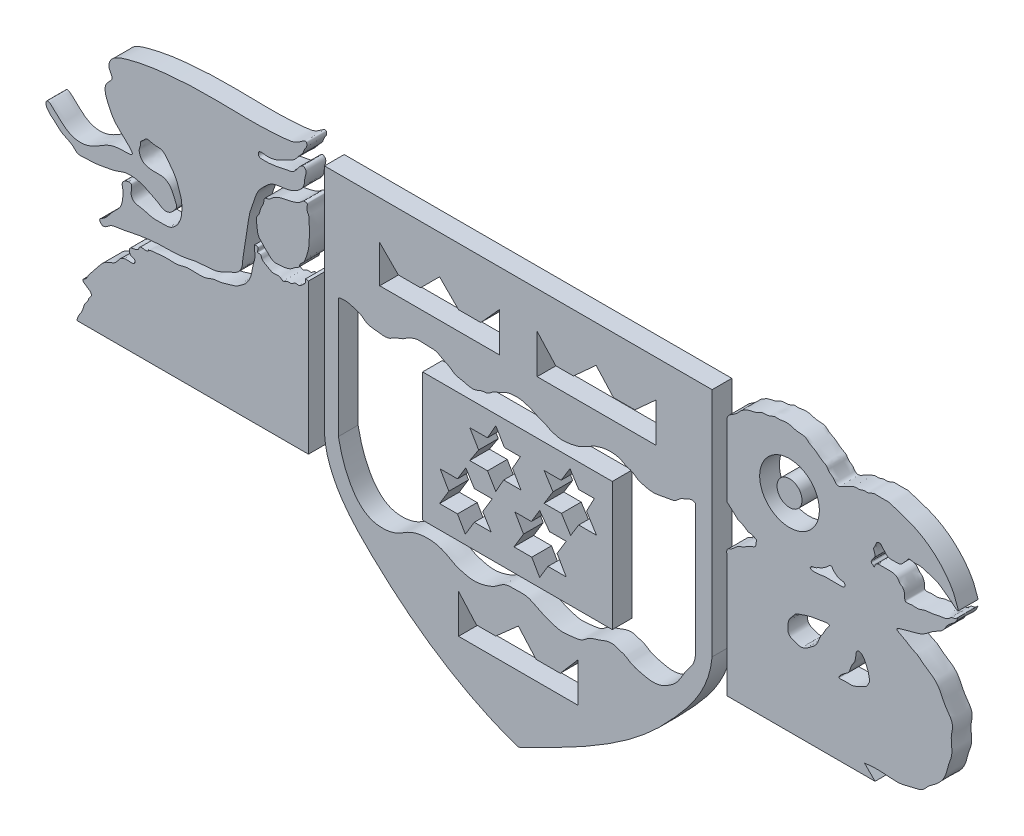
SolidWorks part; units mm, degrees
ref_plane "Front Plane" through (0, 0, 0) normal (0, 0, 1) x (1, 0, 0)
ref_plane "Top Plane" through (0, 0, 0) normal (0, 1, 0) x (1, 0, 0)
ref_plane "Right Plane" through (0, 0, 0) normal (1, 0, 0) x (0, 0, -1)
sketch "Sketch2" plane through (0, 0, 0) normal (0, 0, 1) x (1, 0, 0)
  line L0 (-215.1372, 77.2642) -> (-215.1372, -74.9469)
  line L1 (-215.1372, -74.9469) -> (-450.0201, -74.9469)
  line L2 (-198.8778, -48.2651) -> (-198.8778, 186.6255)
  line L3 (-198.8778, 186.6255) -> (194.5594, 186.6255)
  line L4 (194.5594, 186.6255) -> (194.5594, -48.2651)
  line L5 (93.2386, 55.3239) -> (93.2386, -74.9469)
  line L6 (93.2386, -74.9469) -> (-99.2839, -74.9469)
  line L7 (-99.2839, -74.9469) -> (-99.2839, 55.3239)
  line L8 (-99.2839, 55.3239) -> (93.2386, 55.3239)
  line L9 (-21.3572, 109.2692) -> (-142.8036, 109.2692)
  line L10 (-142.8036, 109.2692) -> (-142.8036, 147.2321)
  line L11 (-142.8036, 147.2321) -> (-123.8222, 128.2507)
  line L12 (-123.8222, 128.2507) -> (-101.35, 128.2507)
  line L13 (-101.35, 128.2507) -> (-82.0804, 147.5203)
  line L14 (-82.0804, 147.5203) -> (-62.8107, 128.2507)
  line L15 (-62.8107, 128.2507) -> (-40.2453, 128.2507)
  line L16 (-40.2453, 128.2507) -> (-21.3572, 149.0856)
  line L17 (-21.3572, 149.0856) -> (-21.3572, 109.2692)
  line L18 (16.9702, 109.2692) -> (137.8333, 109.2692)
  line L19 (137.8333, 109.2692) -> (137.8333, 149.3114)
  line L20 (137.8333, 149.3114) -> (116.1682, 129.6715)
  line L21 (116.1682, 129.6715) -> (94.4529, 129.6715)
  line L22 (94.4529, 129.6715) -> (76.8102, 149.1334)
  line L23 (76.8102, 149.1334) -> (53.8002, 128.2742)
  line L24 (53.8002, 128.2742) -> (35.8796, 128.2742)
  line L25 (35.8796, 128.2742) -> (16.9702, 149.1334)
  line L26 (16.9702, 149.1334) -> (16.9702, 109.2692)
  line L27 (-62.8107, -158.838) -> (58.6041, -158.838)
  line L28 (58.6041, -158.838) -> (58.6041, -118.6788)
  line L29 (58.6041, -118.6788) -> (40.4359, -139.7384)
  line L30 (40.4359, -139.7384) -> (15.8692, -139.7384)
  line L31 (15.8692, -139.7384) -> (-2.1033, -119.4417)
  line L32 (-2.1033, -119.4417) -> (-25.0247, -139.7384)
  line L33 (-25.0247, -139.7384) -> (-44.6466, -139.7384)
  line L34 (-44.6466, -139.7384) -> (-62.8107, -119.2253)
  line L35 (-62.8107, -119.2253) -> (-62.8107, -158.838)
  line L36 (-184.7839, 77.8093) -> (-184.7839, -44.2697)
  line L37 (177.9219, 77.8093) -> (177.9219, -44.2697)
  line L38 (-33.3988, 30.3852) -> (-25.0247, 45.1364)
  line L39 (-25.0247, 45.1364) -> (-16.2196, 30.3852)
  line L40 (-16.2196, 30.3852) -> (0, 30.3852)
  line L41 (0, 30.3852) -> (-8.1098, 16.0997)
  line L42 (-8.1098, 16.0997) -> (0.6485, 1.4268)
  line L43 (0.6485, 1.4268) -> (-17.0156, 1.4268)
  line L44 (-17.0156, 1.4268) -> (-25.0247, -12.6811)
  line L45 (-25.0247, -12.6811) -> (-33.3988, 1.3482)
  line L46 (-33.3988, 1.3482) -> (-51.4405, 1.3482)
  line L47 (-51.4405, 1.3482) -> (-42.4197, 15.1441)
  line L48 (-42.4197, 15.1441) -> (-51.4405, 30.2567)
  line L49 (-51.4405, 30.2567) -> (-33.3988, 30.3852)
  line L50 (24.0411, 1.4268) -> (33.0689, 16.0997)
  line L51 (33.0689, 16.0997) -> (24.0411, 30.3852)
  line L52 (24.0411, 30.3852) -> (41.2768, 30.3852)
  line L53 (41.2768, 30.3852) -> (50.3528, 45.1364)
  line L54 (50.3528, 45.1364) -> (59.1724, 31.1803)
  line L55 (59.1724, 31.1803) -> (75.0124, 31.1803)
  line L56 (75.0124, 31.1803) -> (67.0924, 16.0997)
  line L57 (67.0924, 16.0997) -> (77.2667, 0)
  line L58 (77.2667, 0) -> (59.1724, 0)
  line L59 (59.1724, 0) -> (50.9753, -13.3227)
  line L60 (50.9753, -13.3227) -> (41.6543, 1.4268)
  line L61 (41.6543, 1.4268) -> (24.0411, 1.4268)
  line L62 (19.5246, -7.0232) -> (11.078, -20.9755)
  line L63 (11.078, -20.9755) -> (-5.5411, -20.9755)
  line L64 (-5.5411, -20.9755) -> (3.137, -36.0467)
  line L65 (3.137, -36.0467) -> (-6.5848, -52.1054)
  line L66 (-6.5848, -52.1054) -> (11.5392, -52.1054)
  line L67 (11.5392, -52.1054) -> (19.5246, -65.9733)
  line L68 (19.5246, -65.9733) -> (27.9801, -52.0062)
  line L69 (27.9801, -52.0062) -> (46.4812, -52.0062)
  line L70 (46.4812, -52.0062) -> (37.2306, -35.9411)
  line L71 (37.2306, -35.9411) -> (46.4812, -20.6609)
  line L72 (46.4812, -20.6609) -> (29.6207, -20.6609)
  line L73 (29.6207, -20.6609) -> (19.5246, -7.0232)
  line L74 (-63.8781, -20.9755) -> (-81.4508, -20.9755)
  line L75 (-81.4508, -20.9755) -> (-72.6644, -36.2345)
  line L76 (-72.6644, -36.2345) -> (-82.0804, -51.7881)
  line L77 (-82.0804, -51.7881) -> (-63.8781, -51.7881)
  line L78 (-63.8781, -51.7881) -> (-55.8947, -65.6526)
  line L79 (-55.8947, -65.6526) -> (-46.7831, -50.6019)
  line L80 (-46.7831, -50.6019) -> (-29.7564, -50.6019)
  line L81 (-29.7564, -50.6019) -> (-38.2698, -36.8433)
  line L82 (-38.2698, -36.8433) -> (-28.6635, -20.9755)
  line L83 (-28.6635, -20.9755) -> (-46.7831, -20.9755)
  line L84 (-46.7831, -20.9755) -> (-55.4163, -7.0232)
  line L85 (-55.4163, -7.0232) -> (-63.8781, -20.9755)
  line L86 (209.5236, 168.4535) -> (209.5236, 95.674)
  line L87 (209.5236, 50.21) -> (209.5236, -74.9469)
  line L88 (209.5236, -74.9469) -> (359.9567, -74.9469)
  line L89 (359.9567, -74.9469) -> (349.2206, -64.2108)
  circle A0 centre (273.1415, 134.9863) radius 12.6897
  circle A1 centre (273.1415, 134.9863) radius 30.288
  spline S0 degree 3 poles (-481.6838, 97.9855) (-481.1686, 109.2139) (-458.8842, 78.7668) (-432.2978, 84.6758) (-415.3851, 99.4801) (-383.802, 96.0538) (-410.3287, 114.896) (-417.7314, 129.6658) (-425.6181, 146.3468) (-411.7703, 155.3903) (-419.1213, 163.1906) (-415.6968, 174.0032) (-403.8671, 179.0192) (-389.0534, 182.7717) (-370.9088, 186.1491) (-350.3654, 188.189) (-325.9159, 189.5848) (-301.2341, 189.3671) (-275.3819, 188.7985) (-254.4865, 189.082) (-236.5609, 190.5012) (-226.4732, 192.4326) (-216.8608, 201.2071) (-216.4924, 194.1933) (-219.5765, 191.3548) (-220.2906, 186.6771) (-224.8567, 182.8078) (-228.5214, 176.666) (-236.7832, 172.7326) (-246.5316, 167.4529) (-255.5129, 165.0371) (-265.9387, 167.4603) (-266.2495, 160.8937) (-257.8218, 160.4797) (-248.9482, 161.2808) (-238.5704, 163.896) (-227.5443, 165.279) (-222.5828, 178.6879) (-216.5087, 172.3772) (-219.372, 166.5665) (-218.7208, 158.9455) (-225.3493, 150.9425) (-237.4815, 145.7841) (-251.4122, 146.2964) (-259.735, 138.0605) (-267.4674, 130.6535) (-270.4753, 119.4147) (-275.204, 107.5973) (-276.1987, 98.2613) (-278.3282, 87.6303) (-279.1008, 77.052) (-282.077, 65.5098) (-281.8236, 56.1921) (-286.4704, 48.3421) (-296.362, 45.288) (-308.6114, 37.5073) (-325.5855, 39.0464) (-343.4863, 33.7176) (-359.9554, 34.1106) (-374.5377, 33.2942) (-389.8947, 31.2009) (-403.6843, 27.6252) (-416.7161, 26.6361) (-423.1305, 18.7346) (-428.6374, 25.9698) (-420.5118, 29.2) (-417.0141, 35.5428) (-410.6912, 41.7177) (-404.8713, 47.3766) (-403.5679, 55.8541) (-402.9873, 63.0347) (-405.7642, 71.3845) (-392.65, 75.5095) (-395.3366, 66.5932) (-395.1173, 61.449) (-391.128, 57.0647) (-382.9451, 56.92) (-374.2352, 52.9811) (-364.4716, 53.929) (-356.4468, 53.3119) (-350.2782, 57.3274) (-346.1057, 62.856) (-343.7117, 70.0952) (-343.6262, 77.5663) (-343.792, 84.2958) (-346.3296, 91.1063) (-348.3693, 98.1121) (-352.3991, 105.3601) (-356.8118, 110.4816) (-359.969, 115.0122) (-364.6707, 119.2408) (-371.8169, 117.6815) (-379.4146, 121.5116) (-382.546, 116.828) (-386.3377, 115.1333) (-385.4465, 110.669) (-387.0035, 107.9161) (-386.9218, 104.4107) (-385.7325, 101.4074) (-383.3289, 97.6107) (-377.084, 95.1772) (-369.5759, 95.1569) (-362.0201, 95.431) (-356.9546, 92.1652) (-353.9578, 88.4603) (-352.21, 83.928) (-350.3508, 80.3302) (-348.8858, 76.9159) (-349.2581, 73.625) (-351.6307, 71.1467) (-354.3781, 67.6488) (-359.5109, 65.5933) (-364.4815, 67.4179) (-368.7298, 70.8444) (-374.0969, 72.8061) (-379.1033, 75.9451) (-384.0337, 77.7485) (-389.15, 79.5561) (-395.2265, 80.0253) (-401.4198, 79.7997) (-407.1079, 77.4707) (-413.0764, 75.5422) (-418.8819, 74.4965) (-425.2832, 73.1779) (-433.5228, 72.1892) (-441.7338, 72.2123) (-449.4245, 71.3966) (-452.4807, 74.8747) (-457.2826, 79.0979) (-465.7959, 81.4949) (-471.3355, 87.9923) (-476.2555, 91.4497) (-479.0958, 94.8706) (-481.6838, 97.9855) (-481.1686, 109.2139) (-458.8842, 78.7668) knots -0.009663 -0.0058 -0.002444 0 0.017705 0.043382 0.063353 0.07559 0.09589 0.105371 0.122865 0.129645 0.136402 0.142815 0.154225 0.16544 0.180768 0.198972 0.215876 0.24048 0.259274 0.278734 0.292309 0.301056 0.30813 0.310916 0.313832 0.318232 0.32156 0.328065 0.335249 0.343314 0.354742 0.360031 0.362485 0.366861 0.376163 0.386746 0.392023 0.403564 0.405219 0.41082 0.416796 0.423753 0.434079 0.448614 0.45498 0.461869 0.474526 0.482328 0.493002 0.497202 0.508807 0.518781 0.526208 0.531078 0.539795 0.550325 0.565936 0.579331 0.595672 0.60575 0.614994 0.633506 0.640077 0.647401 0.65101 0.65491 0.663775 0.669553 0.676301 0.682985 0.689559 0.694461 0.701722 0.707403 0.710306 0.714724 0.720005 0.729592 0.737422 0.743696 0.748614 0.754589 0.760379 0.766858 0.772776 0.776613 0.784493 0.790565 0.796683 0.800889 0.80421 0.811211 0.818164 0.819669 0.82442 0.826202 0.829882 0.831776 0.834556 0.837703 0.84244 0.849959 0.856253 0.86021 0.864171 0.867706 0.871987 0.874098 0.876683 0.87948 0.882251 0.887599 0.891481 0.894602 0.900885 0.905226 0.908976 0.91367 0.918397 0.923777 0.928593 0.93327 0.939087 0.942952 0.949254 0.959103 0.963941 0.966225 0.969932 0.979611 0.986702 0.990337 0.9942 0.997556 1 1.017705 1.043382 1.063353 only from (-481.3655, 101.5851) to (-481.3655, 101.5851)
  spline S1 degree 3 poles (-218.4258, 145.0577) (-215.1861, 145.6277) (-217.9586, 139.0421) (-214.4707, 135.5343) (-214.6548, 130.8669) (-214.5201, 126.6626) (-214.0037, 122.5879) (-214.2063, 118.5026) (-214.3431, 114.1944) (-214.3829, 109.6121) (-215.2054, 104.3092) (-216.5316, 99.7852) (-218.0977, 95.4284) (-219.456, 91.0718) (-223.7827, 88.9185) (-224.4921, 83.9458) (-229.0184, 82.6197) (-232.1124, 79.2985) (-238.1302, 76.8659) (-243.8862, 76.6709) (-249.9738, 76.1958) (-253.6384, 78.4092) (-256.4027, 81.7487) (-259.8725, 84.2045) (-262.0072, 87.2883) (-265.0369, 89.7982) (-266.9385, 93.712) (-267.0928, 98.4317) (-268.0942, 103.0975) (-268.1434, 107.8479) (-264.3719, 111.5098) (-264.2405, 117.6013) (-259.9737, 121.9169) (-260.6973, 128.5175) (-255.0684, 128.5805) (-251.9602, 132.2562) (-247.5952, 134.8321) (-243.1532, 136.4237) (-237.5518, 137.4189) (-232.0862, 138.6965) (-226.3652, 140.4649) (-222.7816, 142.6752) (-220.4225, 145.2934) (-218.4258, 145.0577) (-215.1861, 145.6277) (-217.9586, 139.0421) knots -0.030519 -0.013616 -0.008398 0 0.028025 0.053073 0.072938 0.095208 0.117974 0.134884 0.157284 0.183516 0.204379 0.238643 0.254742 0.275232 0.305719 0.319238 0.345145 0.36747 0.388393 0.441113 0.45498 0.479822 0.501596 0.521231 0.543541 0.557889 0.580573 0.606863 0.628752 0.654184 0.67366 0.704075 0.739613 0.763031 0.782855 0.808328 0.834514 0.858982 0.87968 0.920777 0.944636 0.969481 0.986384 0.991602 1 1.028025 1.053073 1.072938 only from (-216.9511, 145.125) to (-216.9511, 145.125)
  spline S2 degree 3 poles (-450.0201, -74.9469) (-449.7833, -69.8714) (-444.0549, -65.3486) (-443.0964, -56.8405) (-438.9983, -53.1908) (-438.2034, -48.7323) (-435.3945, -46.551) (-435.3783, -43.6446) (-437.4013, -41.8397) (-439.7511, -40.624) (-441.572, -38.7287) (-444.1546, -37.8382) (-444.1742, -35.157) (-440.8316, -34.101) (-439.2185, -30.4044) (-436.6135, -26.7596) (-433.6656, -22.9691) (-430.0858, -19.2329) (-427.1125, -14.7509) (-423.7177, -10.9688) (-418.3093, -7.3212) (-410.4912, -5.8224) (-406.2942, 3.1611) (-398.6163, 4.2476) (-392.5475, 3.0003) (-391.0583, 5.6099) (-390.8909, 8.4538) (-395.768, 8.4722) (-397.0769, 12.3869) (-396.3342, 17.8503) (-388.1088, 15.658) (-386.3663, 23.816) (-379.9418, 20.179) (-376.3146, 24.0607) (-369.837, 24.5051) (-363.1973, 25.4309) (-354.9583, 25.4189) (-347.3281, 24.604) (-339.6444, 27.9365) (-331.6742, 27.2721) (-324.6166, 27.2279) (-317.8686, 27.9201) (-311.8804, 31.1511) (-303.0969, 31.1188) (-295.3957, 34.5468) (-288.1706, 35.7986) (-284.5767, 38.9828) (-278.8788, 42.3151) (-274.7337, 48.4085) (-272.4926, 56.1242) (-271.7178, 62.4445) (-269.8153, 68.2732) (-269.0437, 72.8088) (-269.8853, 76.2187) (-269.9418, 78.6954) (-269.6012, 81.0098) (-270.0389, 81.5672) knots 0 0 0 0 0.047872 0.066459 0.082725 0.1008 0.10993 0.116246 0.127541 0.135109 0.143157 0.154807 0.157507 0.168138 0.183324 0.197615 0.213721 0.232111 0.250063 0.268335 0.283322 0.316033 0.343418 0.373101 0.390343 0.396144 0.401833 0.415503 0.431642 0.437475 0.467947 0.480849 0.503639 0.515548 0.530332 0.567146 0.584761 0.613988 0.643782 0.666902 0.694106 0.716003 0.734802 0.761919 0.802723 0.820049 0.83461 0.850441 0.887131 0.905259 0.932159 0.951457 0.967645 0.978258 0.985865 0.995157 0.995157 0.995157 0.995157
  spline S3 degree 3 poles (-270.0389, 81.5672) (-269.813, 81.6505) (-265.2301, 82.3962) (-266.4571, 79.5425) (-267.1731, 75.8277) (-263.4193, 77.2055) (-262.7532, 71.9495) (-256.9908, 69.7885) (-251.393, 64.9997) (-244.7076, 67.7451) (-240.6131, 62.8323) (-236.7416, 67.34) (-232.0008, 65.3627) (-229.1792, 69.6888) (-224.3129, 67.7217) (-220.6226, 71.6415) (-217.338, 74.3201) (-218.3249, 78.039) (-216.9946, 77.8847) (-215.7405, 77.4198) (-215.1372, 77.2642) knots -0.003182 -0.003182 -0.003182 -0.003182 0 0.058316 0.090029 0.118904 0.171051 0.251574 0.371644 0.456215 0.511489 0.583929 0.637245 0.696303 0.756006 0.818658 0.905355 0.924418 0.939066 0.955633 0.955633 0.955633 0.955633
  spline S4 degree 3 poles (-198.8778, -48.2651) (-197.8829, -70.5276) (-183.2427, -98.6357) (-119.714, -164.8031) (-60.9294, -205.761) (-2.1033, -226.0092) knots 0 0 0 0 0.239264 0.32803 1 1 1 1
  spline S5 degree 3 poles (194.5594, -48.2651) (191.8103, -80.0075) (168.9238, -107.5676) (106.1674, -173.9926) (47.7428, -201.4292) (-2.1033, -226.0092) knots 0 0 0 0 0.32923 0.37905 1 1 1 1
  spline S6 degree 3 poles (-184.7839, 77.8093) (-178.2736, 79.9035) (-170.2532, 77.3879) (-161.0664, 74.1337) (-157.1169, 70.1386) (-151.7955, 68.4188) (-146.2153, 68.1313) (-139.9566, 67.1013) (-133.1286, 67.0141) (-127.7425, 71.6291) (-122.3777, 72.8669) (-117.3548, 75.3022) (-113.5226, 78.6078) (-109.328, 79.7167) (-104.4843, 81.7244) (-97.7491, 80.4562) (-90.6622, 80.9818) (-84.9655, 80.3703) (-81, 78.0091) (-77.1355, 75.8296) (-72.9226, 74.2394) (-69.7028, 71.9017) (-65.386, 68.5281) (-58.9667, 68.3927) (-52.229, 65.9003) (-45.4336, 65.6098) (-39.4709, 69.2945) (-32.5296, 68.8249) (-28.1077, 74.0789) (-22.1539, 75.529) (-16.9813, 78.3978) (-11.8655, 80.7476) (-6.3963, 80.9548) (-1.4348, 81.2934) (2.665, 80.4476) (6.4758, 79.3278) (10.1203, 78.2732) (14.1707, 76.2635) (18.2619, 74.2933) (22.6036, 72.719) (26.7415, 71.2081) (30.732, 68.5976) (35.546, 67.3716) (40.4297, 66.1054) (45.7199, 66.279) (51.5592, 67.087) (57.4292, 68.2664) (62.0539, 70.1603) (65.5486, 72.4365) (69.5242, 73.729) (73.3108, 76.8372) (77.2695, 78.1243) (85.3846, 80.7019) (94.0154, 81.3495) (103.0334, 78.6078) (106.8349, 75.7498) (111.5711, 74.9361) (115.5466, 72.6964) (119.3721, 69.501) (126.3056, 67.7099) (133.2599, 65.8056) (141.6392, 67.0709) (148.8073, 68.8849) (157.1521, 69.2356) (161.8434, 75.1226) (169.2964, 77.2582) (174.6275, 81.1652) (177.9219, 77.8093) knots 0 0 0 0 0.049408 0.065122 0.074372 0.092394 0.106765 0.117844 0.14218 0.155822 0.171146 0.184312 0.199027 0.209637 0.217701 0.23937 0.260408 0.273654 0.282771 0.295927 0.30826 0.317462 0.326842 0.350181 0.364489 0.383112 0.400305 0.417495 0.43281 0.449694 0.46396 0.478948 0.492747 0.506085 0.517509 0.525005 0.53703 0.546899 0.560103 0.572321 0.582811 0.594264 0.609033 0.621099 0.633346 0.6498 0.667026 0.679735 0.688384 0.699341 0.711839 0.725848 0.731279 0.77823 0.789511 0.804052 0.814255 0.826241 0.839144 0.852468 0.881209 0.894273 0.917552 0.939885 0.954673 0.972449 1 1 1 1
  spline S7 degree 3 poles (209.5236, 95.674) (212.5405, 93.3286) (216.2863, 89.7451) (221.5347, 84.4717) (227.1006, 83.5216) (230.6308, 79.3938) (235.3227, 79.946) (237.3678, 78.0388) (240.263, 77.1889) (238.5806, 74.0913) (239.2501, 71.402) (236.8882, 69.3307) (233.1389, 68.6546) (229.4752, 65.9879) (225.2648, 63.5187) (221.4707, 62.8181) (218.7229, 60.2311) (216.1788, 57.9819) (213.7106, 56.0047) (210.0409, 55.016) (208.8972, 51.998) (209.5236, 50.21) knots 0 0 0 0 0.140698 0.20272 0.27294 0.34541 0.38802 0.434701 0.45017 0.487486 0.528266 0.550953 0.595482 0.670909 0.718195 0.780085 0.810483 0.858459 0.909934 0.926876 1 1 1 1
  spline S8 degree 3 poles (-184.7839, -44.2697) (-181.7088, -61.1886) (-169.8303, -100.1744) (-136.5071, -103.015) (-124.0018, -99.6314) (-111.7128, -90.5566) (-97.7814, -87.5618) (-84.5209, -89.0586) (-75.9028, -92.1475) (-67.7849, -97.4351) (-58.0622, -100.6848) (-46.9542, -103.0273) (-35.54, -100.778) (-24.7117, -96.5867) (-16.4137, -88.639) (-4.6554, -89.1582) (6.7166, -87.9784) (17.8071, -94.4216) (28.9505, -99.0034) (41.4, -103.2427) (52.4745, -101.3014) (63.0582, -100.4236) (69.7589, -93.0963) (78.5763, -91.56) (85.8589, -88.237) (93.4564, -86.5255) (100.2928, -89.1975) (106.7757, -91.1425) (113.3796, -96.4378) (122.1179, -98.2392) (132.394, -100.8605) (142.436, -100.1127) (151.2298, -94.9571) (158.6125, -89.3821) (163.7989, -81.0288) (168.8305, -72.345) (178.3532, -61.9741) (177.9347, -50.8033) (177.9219, -44.2697) knots 0 0 0 0 0.151714 0.184463 0.215868 0.236778 0.286538 0.30644 0.326271 0.347459 0.37124 0.394882 0.422889 0.447853 0.472851 0.495567 0.523749 0.548118 0.578983 0.60602 0.634174 0.654028 0.674894 0.696728 0.712285 0.72918 0.747028 0.760411 0.774532 0.802842 0.818868 0.846204 0.867455 0.886772 0.907773 0.932716 0.954701 1 1 1 1
  spline S9 degree 3 poles (309.8333, 34.1404) (316.6146, 41.2133) (303.7301, 38.812) (297.5827, 37.9698) (290.7838, 36.2283) (284.7446, 34.028) (278.8715, 32.1557) (276.4822, 28.1432) (273.6412, 25.4911) (271.8583, 21.9888) (271.5257, 17.4086) (270.9, 12.7769) (274.0457, 8.4589) (278.4602, 7.6459) (282.0627, 5.453) (286.3477, 5.5808) (290.389, 7.1494) (294.0315, 10.0777) (298.1916, 12.8743) (302.0858, 17.6088) (303.6178, 24.005) (308.1075, 29.2976) (309.8333, 34.1404) (316.6146, 41.2133) (303.7301, 38.812) knots -0.144306 -0.096104 -0.040352 0 0.085362 0.137297 0.189091 0.255237 0.30617 0.336249 0.370221 0.40499 0.432327 0.487231 0.517287 0.557452 0.596745 0.621659 0.663201 0.704644 0.739875 0.790531 0.855694 0.903896 0.959648 1 1.085362 1.137297 1.189091 only from (313.5092, 38.779) to (313.5092, 38.779)
  spline S10 degree 3 poles (327.1954, -2.1998) (320.4529, -3.3926) (328.3798, 4.5178) (333.6973, 6.801) (334.9591, 12.1651) (336.7735, 16.4227) (339.4403, 19.546) (340.0131, 22.952) (340.6717, 26.3499) (340.3976, 30.0629) (343.7779, 31.5214) (346.957, 30.2022) (349.3102, 26.758) (351.0622, 22.5456) (353.0966, 18.2625) (353.6496, 14.1079) (354.9822, 10.1264) (352.7781, 7.3256) (351.9419, 4.1499) (348.8486, 2.9463) (346.2825, 1.3535) (343.4885, 0.1584) (340.5104, -1.1685) (337.0704, -2.6599) (333.0722, -2.1703) (330.0308, -2.2837) (327.1954, -2.1998) (320.4529, -3.3926) (328.3798, 4.5178) knots -0.088046 -0.056647 -0.043591 0 0.081736 0.133987 0.190844 0.228094 0.273758 0.308804 0.327816 0.379241 0.399302 0.425337 0.474278 0.518835 0.562011 0.613036 0.645893 0.676772 0.712537 0.736357 0.769865 0.80361 0.825904 0.867284 0.911954 0.943353 0.956409 1 1.081736 1.133987 1.190844 only from (323.727, -2.2577) to (323.727, -2.2577)
  spline S11 degree 3 poles (316.1314, 92.1618) (313.5969, 91.9591) (312.1142, 89.8009) (309.7031, 88.0861) (307.4849, 86.6279) (305.2156, 84.8586) (302.3665, 84.5308) (299.5874, 81.9083) (295.8269, 82.5552) (292.5785, 78.0037) (303.5528, 78.2401) (308.2952, 79.6506) (313.9146, 79.4569) (318.5657, 79.4715) (323.1132, 79.6003) (326.5095, 79.2857) (329.6202, 80.081) (329.472, 84.5246) (325.4535, 84.5556) (322.1751, 85.2977) (320.2667, 87.1881) (318.0856, 88.4831) (317.0279, 90.0964) (316.1314, 92.1618) (313.5969, 91.9591) (312.1142, 89.8009) knots -0.073572 -0.035714 -0.013755 0 0.049661 0.077696 0.112101 0.150352 0.184064 0.215872 0.288688 0.300787 0.407002 0.496219 0.54632 0.609677 0.675012 0.71584 0.741618 0.783753 0.828468 0.86941 0.912101 0.926428 0.964286 0.986245 1 1.049661 1.077696 1.112101 only from (314.703, 91.9811) to (314.703, 91.9811)
  spline S12 degree 3 poles (349.2206, -64.2108) (357.6678, -62.7692) (369.1852, -63.3622) (385.8839, -64.9292) (396.7166, -61.0256) (408.3955, -59.459) (413.9001, -51.6344) (420.9272, -47.3399) (427.3148, -41.4228) (432.4217, -33.2786) (433.9871, -23.0511) (438.045, -14.771) (437.9186, -5.339) (436.4597, 3.5502) (439.67, 12.7728) (436.0968, 20.5289) (430.9435, 26.7364) (427.5117, 34.3397) (423.5745, 42.2834) (416.8083, 47.974) (408.9967, 52.3363) (403.4077, 58.1019) (396.7612, 60.284) (391.6128, 64.2264) (387.0376, 66.359) (379.1841, 70.4715) (388.9484, 72.7951) (394.0051, 74.1679) (400.8106, 76.2129) (410.0698, 78.443) (418.1157, 87.0112) (429.1668, 90.9189) (432.7149, 98.8096) (438.2113, 103.1128) (441.8984, 105.4571) (445.2039, 112.8661) (441.6058, 108.049) (437.5439, 108.7537) (434.426, 104.6425) (429.7226, 103.575) (424.3094, 102.9872) (417.9422, 101.179) (410.7436, 101.2765) (403.7022, 97.7816) (397.6085, 99.41) (388.9998, 96.9927) (390.5204, 104.2817) (389.0097, 107.9164) (387.6481, 110.1566) (384.9289, 111.4047) (383.5985, 114.6865) (379.86, 117.4587) (374.6757, 117.751) (369.5742, 117.6022) (364.4899, 117.8077) (359.9251, 117.1388) (359.1975, 111.7612) (357.7519, 114.5284) (355.2895, 115.38) (357.2693, 118.931) (358.5669, 120.8593) (360.2939, 122.2591) (359.83, 125.4921) (357.5976, 128.8901) (360.63, 132.5619) (361.193, 136.8805) (366.4448, 136.9643) (367.532, 133.5834) (370.2039, 132.0081) (371.9669, 128.8722) (376.22, 128.1182) (379.8101, 128.3306) (383.353, 128.1509) (386.9877, 129.0128) (389.1993, 132.4753) (392.0009, 134.3059) (393.7186, 138.6607) (399.2047, 136.7104) (405.8663, 137.7322) (413.8728, 135.0197) (421.5025, 132.9563) (427.4957, 129.1889) (431.5249, 125.993) (436.6567, 122.6414) (439.264, 119.7973) (445.959, 115.1425) (441.9921, 123.3185) (440.8134, 128.4315) (428.894, 150.3064) (408.7676, 166.5233) (386.7343, 173.1956) (381.5526, 175.3786) (377.2807, 175.9296) (373.6089, 177.8271) (369.5811, 177.3352) (365.9159, 177.5156) (362.3611, 177.4022) (358.9441, 177.7555) (355.8292, 176.2924) (352.6226, 174.7635) (348.378, 175.6809) (344.5263, 173.242) (339.0954, 174.1103) (335.0448, 171.5105) (329.9293, 169.5169) (326.5201, 167.0923) (322.2711, 165.5237) (319.0523, 167.9157) (317.2942, 171.4903) (312.9285, 173.3241) (311.4376, 177.7123) (307.1668, 179.6382) (303.1905, 182.2204) (299.7781, 185.5729) (295.7991, 187.3464) (292.6916, 189.1298) (289.709, 192.6889) (284.5537, 192.9309) (279.5994, 193.224) (274.784, 195.0184) (268.7906, 196.0643) (263.0022, 194.1847) (257.5457, 195.1895) (252.391, 191.5014) (245.6596, 192.9019) (240.4389, 189.1604) (235.5233, 187.9758) (230.726, 187.0965) (227.3483, 184.94) (223.7799, 183.1541) (221.1868, 179.6089) (215.583, 174.9775) (210.2448, 172.9302) (209.5236, 168.4535) knots 0 0 0 0 0.031361 0.043465 0.061521 0.074158 0.084973 0.095187 0.10474 0.117217 0.130046 0.142913 0.150736 0.164686 0.176248 0.184988 0.19487 0.206408 0.215856 0.227585 0.238505 0.249278 0.256639 0.264308 0.272368 0.278549 0.286957 0.295021 0.302068 0.312509 0.330138 0.344439 0.353291 0.36127 0.368641 0.374074 0.377474 0.38305 0.388661 0.394518 0.400489 0.409061 0.418936 0.427069 0.436548 0.443557 0.451728 0.455346 0.458867 0.460991 0.466115 0.471206 0.477466 0.484934 0.490191 0.496906 0.500021 0.502694 0.504368 0.509063 0.512754 0.51437 0.516689 0.523824 0.527197 0.533341 0.537535 0.542148 0.54487 0.548855 0.554801 0.559382 0.56247 0.568088 0.572092 0.577186 0.580516 0.587439 0.593758 0.60661 0.617529 0.623293 0.632704 0.636963 0.645412 0.650355 0.657189 0.665181 0.674554 0.745433 0.754859 0.760344 0.76626 0.770783 0.775259 0.780947 0.784509 0.788535 0.793454 0.79705 0.801465 0.808729 0.812625 0.821182 0.82557 0.833079 0.837069 0.841063 0.846511 0.851673 0.857442 0.862239 0.868392 0.875246 0.879744 0.884522 0.888517 0.896413 0.902144 0.9072 0.91542 0.924216 0.929356 0.935086 0.946295 0.95227 0.95813 0.965047 0.970182 0.972933 0.979796 0.986043 1 1 1 1
extrude "Boss-Extrude3" add sketch "Sketch2" along normal blind 20 contours S5 L4 L3 L2 S4 S8 L36 S6 L37 L35 L34 L33 L32 L31 L30 L29 L28 L27 L26 L25 L24 L23 L22 L21 L20 L19 L18 L16 L17 L9 L10 L11 L12 L13 L14 L15 | L89 S12 L86 S7 L87 L88 S10 S9 A1 S11 | A0 | L8 L7 L6 L5 L85 L84 L83 L82 L81 L80 L79 L78 L77 L76 L75 L74 L73 L72 L71 L70 L69 L68 L67 L66 L65 L64 L63 L62 L48 L49 L38 L39 L40 L41 L42 L43 L44 L45 L46 L47 L60 L61 L50 L51 L52 L53 L54 | S3 S2 L1 L0 | S1 | S0
